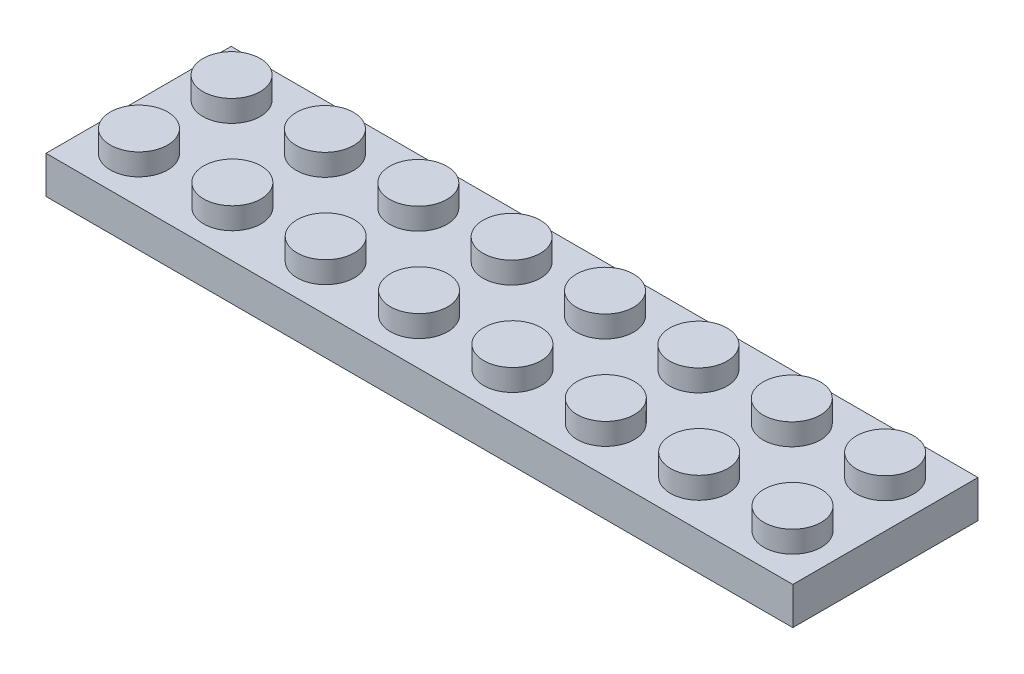
SolidWorks part; units mm, degrees
ref_plane "Front Plane" through (0, 0, 0) normal (0, 0, 1) x (1, 0, 0)
ref_plane "Top Plane" through (0, 0, 0) normal (0, 1, 0) x (1, 0, 0)
ref_plane "Right Plane" through (0, 0, 0) normal (1, 0, 0) x (0, 0, -1)
sketch "Sketch1" plane through (0, 0, 0) normal (0, 1, 0) x (1, 0, 0)
  line L1 (-31.915, 7.915) -> (31.915, 7.915)
  line L2 (-31.915, 7.915) -> (-31.915, -7.915)
  line L3 (-31.915, -7.915) -> (31.915, -7.915)
  line L4 (31.915, 7.915) -> (31.915, -7.915)
  line L5 (-31.915, 7.915) -> (31.915, -7.915) construction
  line L6 (-31.915, -7.915) -> (31.915, 7.915) construction
  point P0 (0, 0)
  dimension "D1" = 15.83
  dimension "D2" = 63.83
extrude "Boss-Extrude1" add sketch "Sketch1" against normal blind 3.2
sketch "Sketch2" plane through (0, 0, 0) normal (0, 1, 0) x (1, 0, 0)
  line L1 (-31.915, 7.915) -> (-31.915, -7.915) construction
  line L2 (31.915, 7.915) -> (-31.915, 7.915) construction
  line L3 (-35.7233, 0) -> (35.2056, 0) construction
  circle A0 centre (-27.9256, 3.9575) radius 2.45
  circle A1 centre (-19.9456, 3.9575) radius 2.45
  circle A2 centre (-11.9656, 3.9575) radius 2.45
  circle A3 centre (-3.9856, 3.9575) radius 2.45
  circle A4 centre (3.9944, 3.9575) radius 2.45
  circle A5 centre (11.9744, 3.9575) radius 2.45
  circle A6 centre (19.9544, 3.9575) radius 2.45
  circle A7 centre (27.9344, 3.9575) radius 2.45
  circle A8 centre (27.9344, -3.9575) radius 2.45
  circle A9 centre (19.9544, -3.9575) radius 2.45
  circle A10 centre (11.9744, -3.9575) radius 2.45
  circle A11 centre (3.9944, -3.9575) radius 2.45
  circle A12 centre (-3.9856, -3.9575) radius 2.45
  circle A13 centre (-11.9656, -3.9575) radius 2.45
  circle A14 centre (-19.9456, -3.9575) radius 2.45
  circle A15 centre (-27.9256, -3.9575) radius 2.45
  dimension "D1" = 4.9
  dimension "D2" = 3.9894
  dimension "D5" = 7.98
  dimension "D3" = 3.9575
  dimension "D4" = 8
extrude "Boss-Extrude2" add sketch "Sketch2" along normal blind 1.85
shell "Shell1" thickness 1.5
sketch "Sketch3" plane through (0, -1.5, 0) normal (0, -1, 0) x (1, 0, 0)
  line L1 (-31.915, -7.915) -> (-31.915, 7.915) construction
  line L2 (31.915, -7.915) -> (-31.915, -7.915) construction
  circle A0 centre (-23.9362, 0) radius 3.24
  circle A1 centre (-23.9362, 0) radius 2.43
  circle A2 centre (-15.9562, 0) radius 3.24
  circle A3 centre (-15.9562, 0) radius 2.43
  circle A4 centre (-7.9762, 0) radius 3.24
  circle A5 centre (-7.9762, 0) radius 2.43
  circle A6 centre (0.0038, 0) radius 3.24
  circle A7 centre (0.0038, 0) radius 2.43
  circle A8 centre (7.9838, 0) radius 3.24
  circle A9 centre (7.9838, 0) radius 2.43
  circle A10 centre (15.9638, 0) radius 3.24
  circle A11 centre (15.9638, 0) radius 2.43
  circle A12 centre (23.9438, 0) radius 3.24
  circle A13 centre (23.9438, 0) radius 2.43
  dimension "D4" = 6.48
  dimension "D5" = 4.86
  dimension "D6" = 7.98
  dimension "D1" = 7.9787
  dimension "D3" = 7.915
  dimension "D2" = 7
extrude "Boss-Extrude3" add sketch "Sketch3" along normal offset from surface (1.5 mm away) 0.2 up to face at (0, -3.2, 0)
